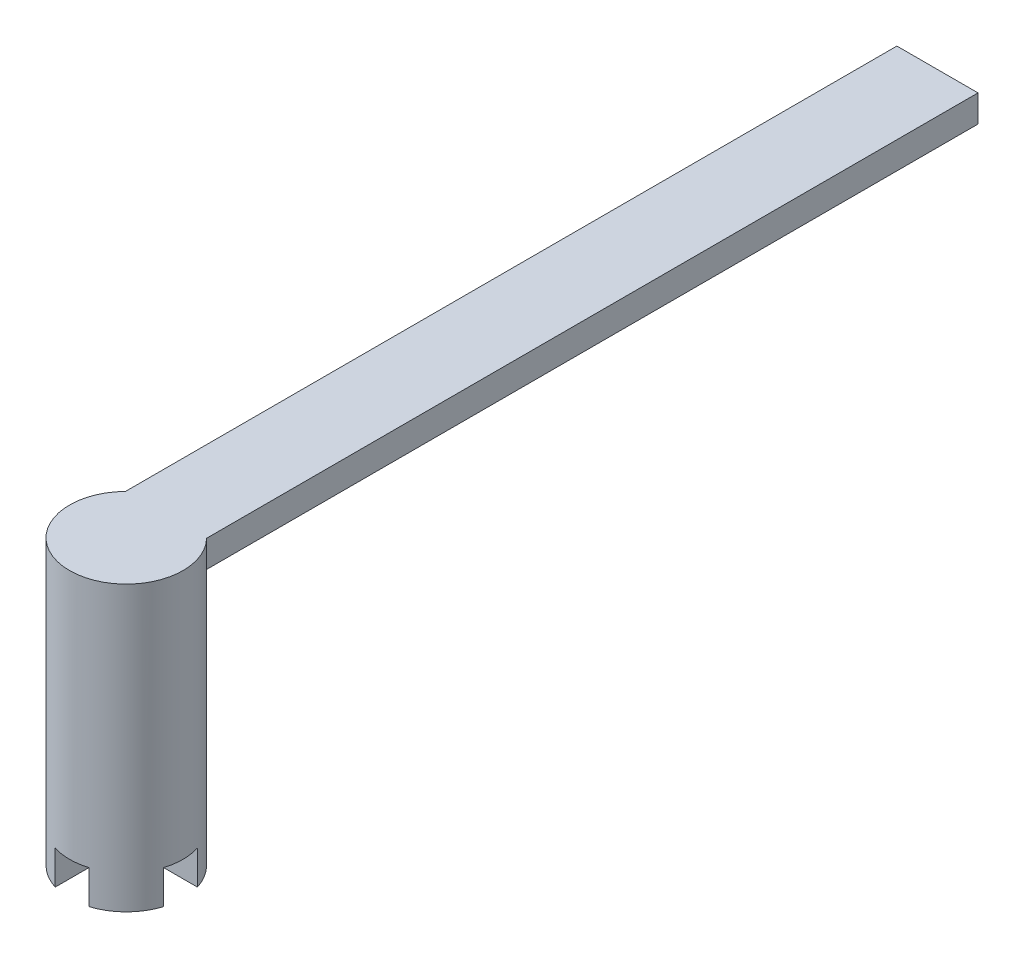
SolidWorks part; units mm, degrees
ref_plane "Front Plane" through (0, 0, 0) normal (0, 0, 1) x (1, 0, 0)
ref_plane "Top Plane" through (0, 0, 0) normal (0, 1, 0) x (1, 0, 0)
ref_plane "Right Plane" through (0, 0, 0) normal (1, 0, 0) x (0, 0, -1)
sketch "Sketch2" plane through (0, 0, 0) normal (0, 1, 0) x (1, 0, 0)
  line L1 (-3.81, 0) -> (3.81, 0)
  line L2 (-3.81, 0) -> (-3.81, 76.2)
  line L3 (-3.81, 76.2) -> (3.81, 76.2)
  line L4 (3.81, 0) -> (3.81, 76.2)
  circle A0 centre (0, 0) radius 5.334
  point P7 (0, 0)
  dimension "D1" = 10.668
  dimension "D2" = 76.2
  dimension "D3" = 7.62
extrude "Boss-Extrude1" add sketch "Sketch2" along normal blind 2.54 contours A0 L4 L1 L2 | L3 A0 | L3 A0
sketch "Sketch3" plane through (0, 0, 0) normal (0, -1, 0) x (1, 0, 0)
  circle A0 centre (0, 0) radius 5.334
  dimension "D1" = 10.668
extrude "Boss-Extrude2" add sketch "Sketch3" along normal blind 24.13
sketch "Sketch4" plane through (0, -24.13, 0) normal (0, -1, 0) x (1, 0, 0)
  line L1 (-1.5875, 6.35) -> (1.5875, 6.35)
  line L2 (-1.5875, 6.35) -> (-1.5875, -6.35)
  line L3 (-1.5875, -6.35) -> (1.5875, -6.35)
  line L4 (1.5875, 6.35) -> (1.5875, -6.35)
  line L5 (-6.35, 1.5875) -> (6.35, 1.5875)
  line L6 (-6.35, 1.5875) -> (-6.35, -1.5875)
  line L7 (-6.35, -1.5875) -> (6.35, -1.5875)
  line L8 (6.35, 1.5875) -> (6.35, -1.5875)
  point P4 (0, 6.35)
  point P6 (1.5875, 0)
  point P11 (6.35, 0)
  point P12 (0, 1.5875)
  circle M1 centre (0, 0) radius 5.334
  dimension "D1" = 3.175
  dimension "D2" = 12.7
  dimension "D3" = 3.175
  dimension "D4" = 12.7
extrude "Cut-Extrude1" cut sketch "Sketch4" against normal blind 3.175 contours L7 L2 L5 M1 | L2 L7 L4 L5 | L2 L5 L4 M1 | L4 L7 L5 M1 | L7 L2 L4 M1
equation "\"D3@Sketch4\"=\"D1@Sketch4\""
equation "\"D4@Sketch4\"=\"D2@Sketch4\""
